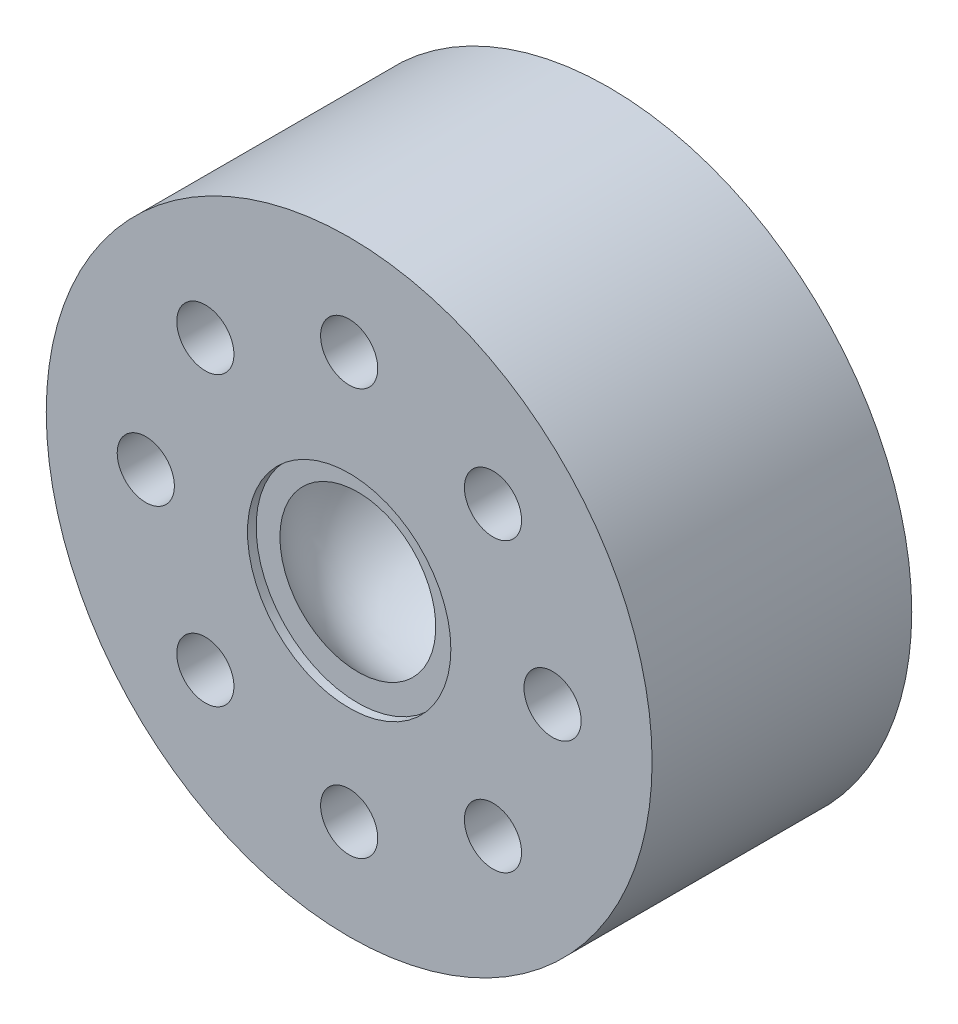
SolidWorks part; units mm, degrees
ref_plane "Front Plane" through (0, 0, 0) normal (0, 0, 1) x (1, 0, 0)
ref_plane "Top Plane" through (0, 0, 0) normal (0, 1, 0) x (1, 0, 0)
ref_plane "Right Plane" through (0, 0, 0) normal (1, 0, 0) x (0, 0, -1)
sketch "Sketch1" plane through (0, 0, 0) normal (0, 0, 1) x (1, 0, 0)
  circle A0 centre (0, 0) radius 35
  dimension "D1" = 70
extrude "Boss-Extrude1" add sketch "Sketch1" along normal blind 50
sketch "Sketch2" plane through (0, 0, 50) normal (0, 0, 1) x (1, 0, 0)
  circle A0 centre (0, -0.3638) radius 11.75
  dimension "D1" = 23.5
extrude "Cut-Extrude1" cut sketch "Sketch2" against normal blind 21
sketch "Sketch3" plane through (0, 0, 29) normal (0, 0, 1) x (1, 0, 0)
  circle A0 centre (0, 0) radius 9
  dimension "D1" = 18
extrude "Cut-Extrude2" cut sketch "Sketch3" against normal blind 5
sketch "Sketch4" plane through (0, 0, 0) normal (1, 0, 0) x (0, 0, -1)
  line L0 (-8.8535, 5) -> (-8.8535, 0)
  line L1 (-8.8535, 0) -> (-29.0145, 0)
  line L2 (-29.0145, 0) -> (-29.0145, 8.9865)
  spline S0 degree 3 poles (-29.0145, 8.9865) (-22.0846, 17.4612) (-14.6113, 9.4232) (-8.8535, 5) knots 0 0 0 0 1 1 1 1
  dimension "D1" = 5
revolve "Cut-Revolve1" cut sketch "Sketch4" angle 360 about L1
sketch "Sketch6" plane through (0, 0, 0) normal (0, 0, -1) x (-1, 0, 0)
  circle A0 centre (0, 0) radius 6.35
  dimension "D1" = 12.7
extrude "Cut-Extrude3" cut sketch "Sketch6" against normal through all
sketch "Sketch7" plane through (0, 0, 50) normal (0, 0, 1) x (1, 0, 0)
  circle A1 centre (0, 0) radius 35
  dimension "D1" = 70
extrude "Cut-Extrude4" cut sketch "Sketch7" against normal blind 20
sketch "Sketch9" plane through (0, 0, 0) normal (0, 0, -1) x (-1, 0, 0)
  circle A0 centre (0, 0) radius 23.5
  circle A1 centre (0, -23.5) radius 3.302
  circle A2 centre (-16.617, -16.617) radius 3.302
  circle A3 centre (-23.5, 0) radius 3.302
  circle A4 centre (-16.617, 16.617) radius 3.302
  circle A5 centre (0, 23.5) radius 3.302
  circle A6 centre (16.617, 16.617) radius 3.302
  circle A7 centre (23.5, 0) radius 3.302
  circle A8 centre (16.617, -16.617) radius 3.302
  point P21 (0, 0)
  dimension "D1" = 47
  dimension "D2" = 6.604
  dimension "D3" = 8
extrude "Cut-Extrude6" cut sketch "Sketch9" against normal through all contours A0 A7 | A0 A7 | A0 A8 | A0 A8 | A0 A1 | A0 A1 | A0 A2 | A0 A2 | A0 A3 | A0 A3 | A0 A4 | A0 A4 | A0 A5 | A0 A5 | A0 A6 | A0 A6
